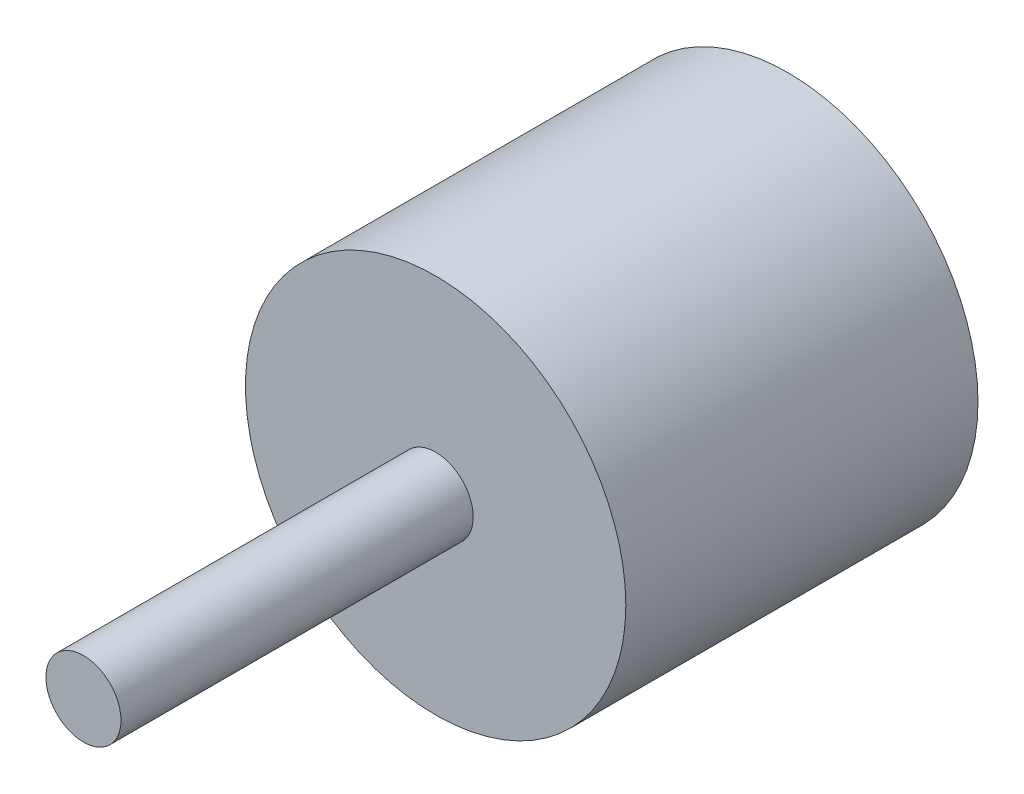
SolidWorks part; units mm, degrees
ref_plane "Front Plane" through (0, 0, 0) normal (0, 0, 1) x (1, 0, 0)
ref_plane "Top Plane" through (0, 0, 0) normal (0, 1, 0) x (1, 0, 0)
ref_plane "Right Plane" through (0, 0, 0) normal (1, 0, 0) x (0, 0, -1)
sketch "Sketch1" plane through (0, 0, 0) normal (0, 0, 1) x (1, 0, 0)
  circle A0 centre (0, 0) radius 26.9982
extrude "Boss-Extrude1" add sketch "Sketch1" along normal blind 50
sketch "Sketch2" plane through (0, 0, 50) normal (0, 0, 1) x (1, 0, 0)
  circle A0 centre (0, 0) radius 5.329
extrude "Boss-Extrude2" add sketch "Sketch2" along normal blind 50
